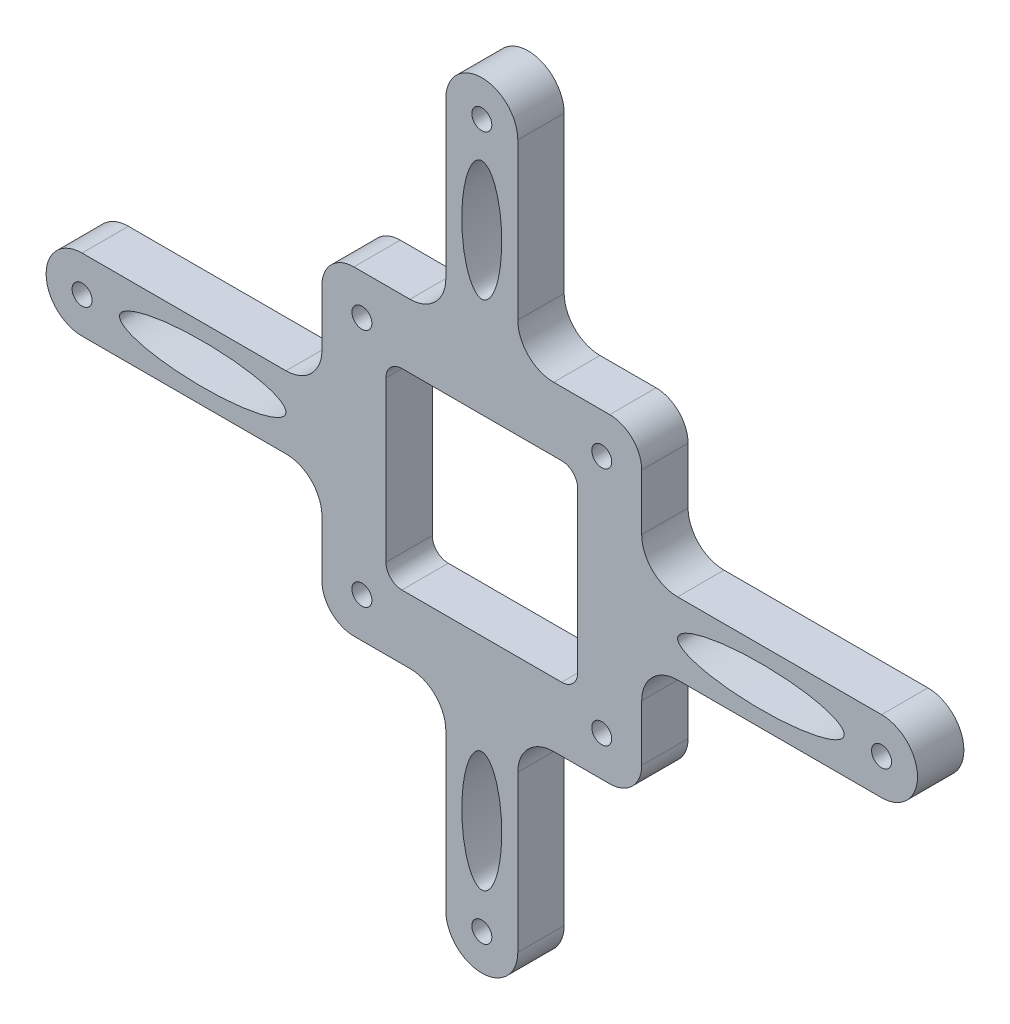
SolidWorks part; units mm, degrees
ref_plane "Front Plane" through (0, 0, 0) normal (0, 0, 1) x (1, 0, 0)
ref_plane "Top Plane" through (0, 0, 0) normal (0, 1, 0) x (1, 0, 0)
ref_plane "Right Plane" through (0, 0, 0) normal (1, 0, 0) x (0, 0, -1)
sketch "Sketch1" plane through (0, 0, 0) normal (0, 0, 1) x (1, 0, 0)
  line L0 (-45.5, 4.5) -> (-45.5, -4.5) construction
  line L1 (0, 20.0016) -> (0, 56.0888) construction
  line L2 (-50, 0) -> (-24.4997, 0.0026) construction
  line L3 (-0.01, -44.01) -> (0, -20) construction
  line L4 (-16, 20) -> (-8.99, 20)
  line L5 (8.99, -20) -> (16, -20)
  line L6 (-20, -20) -> (20, 20) construction
  line L7 (-20, 20) -> (20, -20) construction
  line L8 (4.5, 24.49) -> (4.5, 44)
  line L9 (20, 8.99) -> (20, 16)
  line L10 (-4.5, 24.49) -> (-4.5, 44)
  line L11 (9.9948, -11.9948) -> (-9.9948, -11.9948)
  line L12 (11.9948, -9.9948) -> (11.9948, 9.9948)
  line L13 (9.9948, 11.9948) -> (-9.9948, 11.9948)
  line L14 (-11.9948, -9.9948) -> (-11.9948, 9.9948)
  line L15 (11.9948, -11.9948) -> (-11.9948, 11.9948) construction
  line L16 (11.9948, 11.9948) -> (-11.9948, -11.9948) construction
  line L17 (-0.01, 44.0084) -> (0, 20.0016) construction
  line L18 (8.99, 20) -> (16, 20)
  line L19 (-51.25, 0) -> (-50000, 0) construction
  line L20 (-24.4997, 0.0026) -> (-24.49, -4.5) construction
  line L21 (20, -16) -> (20, -8.99)
  line L22 (-4.5, -24.49) -> (-4.5, -44)
  line L23 (4.5, -24.49) -> (4.5, -44)
  line L24 (-16, -20) -> (-8.99, -20)
  line L25 (1.0007, 0.0051) -> (-0.0055, 0.0055) construction
  line L26 (-20, -16) -> (-20, -8.99)
  line L27 (-24.49, 4.5) -> (-50, 4.5)
  line L28 (24.49, 4.5) -> (50, 4.5)
  line L29 (-20, 8.99) -> (-20, 16)
  line L30 (24.49, -4.5) -> (50, -4.5)
  line L31 (-24.49, -4.5) -> (-50, -4.5)
  line L34 (-0.005, 0.005) -> (1.0007, 0.0051) construction
  circle A0 centre (0, 44) radius 1.25
  circle A1 centre (-15, 15) radius 1.25
  circle A2 centre (15, 15) radius 1.25
  circle A3 centre (15, -15) radius 1.25
  circle A4 centre (-15, -15) radius 1.25
  arc A5 (-4.5, 44) -> (0, 48.5) centre (0, 44) cw
  arc A6 (-4.5, 24.49) -> (-8.99, 20) centre (-8.99, 24.49) cw
  arc A7 (8.99, 20) -> (4.5, 24.49) centre (8.99, 24.49) cw
  arc A8 (0, 48.5) -> (4.5, 44) centre (0, 44) cw
  circle A9 centre (-50, 0) radius 1.25
  arc A10 (20, 8.99) -> (24.49, 4.5) centre (24.49, 8.99) ccw
  arc A11 (24.49, -4.5) -> (20, -8.99) centre (24.49, -8.99) ccw
  circle A12 centre (50, 0) radius 1.25
  arc A14 (0, -48.5) -> (4.5, -44) centre (0, -44) ccw
  arc A15 (8.99, -20) -> (4.5, -24.49) centre (8.99, -24.49) ccw
  arc A16 (-4.5, -24.49) -> (-8.99, -20) centre (-8.99, -24.49) ccw
  arc A17 (-4.5, -44) -> (0, -48.5) centre (0, -44) ccw
  circle A18 centre (0, -44) radius 1.25
  arc A20 (-50, 4.5) -> (-50, -4.5) centre (-50, 0) ccw
  arc A21 (-24.49, -4.5) -> (-20, -8.99) centre (-24.49, -8.99) cw
  arc A22 (-20, 8.99) -> (-24.49, 4.5) centre (-24.49, 8.99) cw
  arc A23 (50, 4.5) -> (50, -4.5) centre (50, 0) cw
  arc A24 (-20, -16) -> (-16, -20) centre (-16, -16) ccw
  arc A25 (16, -20) -> (20, -16) centre (16, -16) ccw
  arc A26 (20, 16) -> (16, 20) centre (16, 16) ccw
  arc A27 (-16, 20) -> (-20, 16) centre (-16, 16) ccw
  arc A28 (-11.9948, -9.9948) -> (-9.9948, -11.9948) centre (-9.9948, -9.9948) ccw
  arc A29 (11.9948, -9.9948) -> (9.9948, -11.9948) centre (9.9948, -9.9948) cw
  arc A30 (9.9948, 11.9948) -> (11.9948, 9.9948) centre (9.9948, 9.9948) cw
  arc A31 (-9.9948, 11.9948) -> (-11.9948, 9.9948) centre (-9.9948, 9.9948) ccw
  ellipse E0 centre (-0.005, 32.005) end of major axis (0, 39.5) minor radius 2.505
  ellipse E2 centre (-0.005, -32.005) end of major axis (0, -39.5) minor radius 2.505
  ellipse E4 centre (-34.9098, 0.0015) end of major axis (-24.4997, 0.0026) minor radius 2.505
  ellipse E5 centre (34.9098, 0.0015) end of major axis (24.4997, 0.0026) minor radius 2.505
  point P5 (0, 0)
  point P17 (0, 0)
  point P44 (4.5, 20)
  point P47 (-4.5, 20)
  point P67 (20, -4.5)
  point P68 (20, 4.5)
  point P86 (-4.5, -20)
  point P87 (4.5, -20)
  point P107 (-20, 4.5)
  point P108 (-20, -4.5)
  dimension "D2" = 2.5
  dimension "D7" = 2.5
  dimension "D9" = 4.25
  dimension "D10" = 4.5
  dimension "D13" = 1.99
  dimension "D4" = 4
  dimension "D5" = 2
  dimension "D6" = 50
  dimension "D1" = 44
  dimension "D3" = 40
  dimension "D8" = 15
  dimension "D11" = 2
  dimension "D12" = 4.5
extrude "Boss-Extrude1" add sketch "Sketch1" along normal blind 5.8
